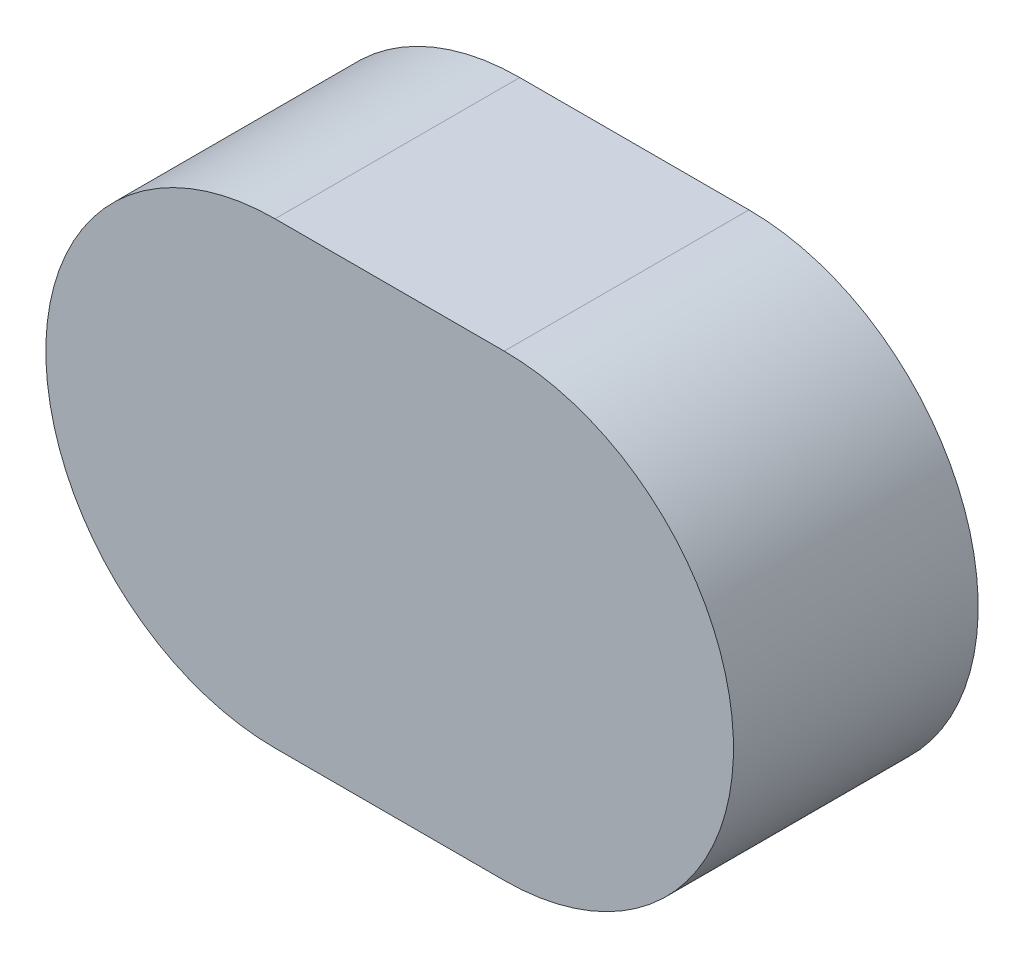
SolidWorks part; units mm, degrees
ref_plane "前视基准面" through (0, 0, 0) normal (0, 0, 1) x (1, 0, 0)
ref_plane "上视基准面" through (0, 0, 0) normal (0, 1, 0) x (1, 0, 0)
ref_plane "右视基准面" through (0, 0, 0) normal (1, 0, 0) x (0, 0, -1)
sketch "草图1" plane through (0, 0, 0) normal (0, 0, 1) x (1, 0, 0)
  line L0 (-17.876, 0) -> (-13.876, 0) construction
  line L1 (-17.876, 4) -> (-13.876, 4)
  line L2 (-17.876, -4) -> (-13.876, -4)
  arc A0 (-17.876, 4) -> (-17.876, -4) centre (-17.876, 0) ccw
  arc A1 (-13.876, -4) -> (-13.876, 4) centre (-13.876, 0) ccw
  point P2 (-15.876, 0)
  dimension "D1" = 8
  dimension "D2" = 12
extrude "凸台-拉伸1" add sketch "草图1" along normal blind 4.27
